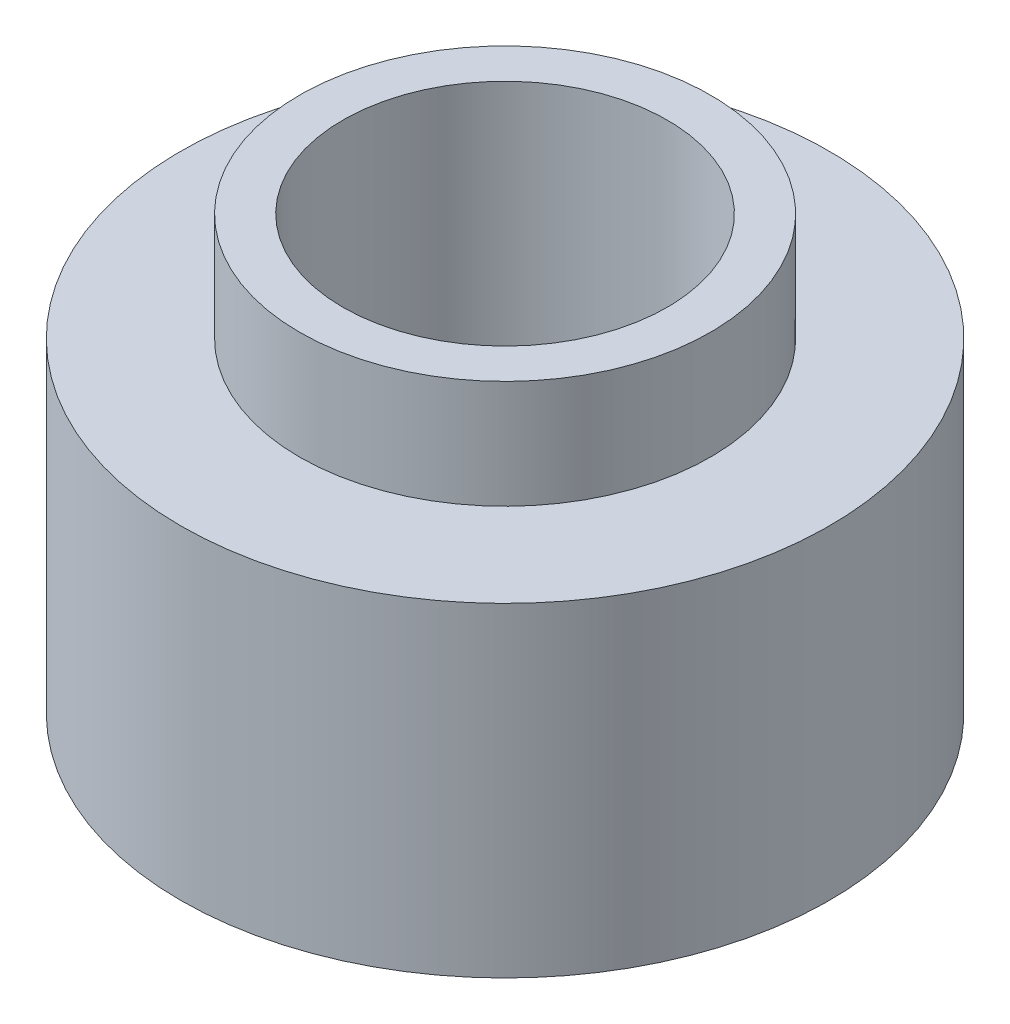
SolidWorks part; units mm, degrees
ref_plane "Front Plane" through (0, 0, 0) normal (0, 0, 1) x (1, 0, 0)
ref_plane "Top Plane" through (0, 0, 0) normal (0, 1, 0) x (1, 0, 0)
ref_plane "Right Plane" through (0, 0, 0) normal (1, 0, 0) x (0, 0, -1)
sketch "Sketch1" plane through (0, 0, 0) normal (0, 1, 0) x (1, 0, 0)
  circle A0 centre (0, 0) radius 0.375
  dimension "D1" = 0.75
extrude "Boss-Extrude2" add sketch "Sketch1" along normal blind 0.375
sketch "Sketch3" plane through (0, 0.375, 0) normal (0, 1, 0) x (1, 0, 0)
  circle A0 centre (0, 0) radius 0.1875
  dimension "D1" = 0.375
extrude "Cut-Extrude1" cut sketch "Sketch3" against normal blind 0.375
sketch "Sketch4" plane through (0, 0.375, 0) normal (0, 1, 0) x (1, 0, 0)
  circle A1 centre (0, 0) radius 0.2375
  dimension "D1" = 0.475
extrude "Boss-Extrude3" add sketch "Sketch4" along normal blind 0.125
sketch "Sketch5" plane through (0, 0.5, 0) normal (0, 1, 0) x (1, 0, 0)
  circle A0 centre (0, 0) radius 0.1875
  dimension "D1" = 0.375
extrude "Cut-Extrude2" cut sketch "Sketch5" against normal blind 0.125
